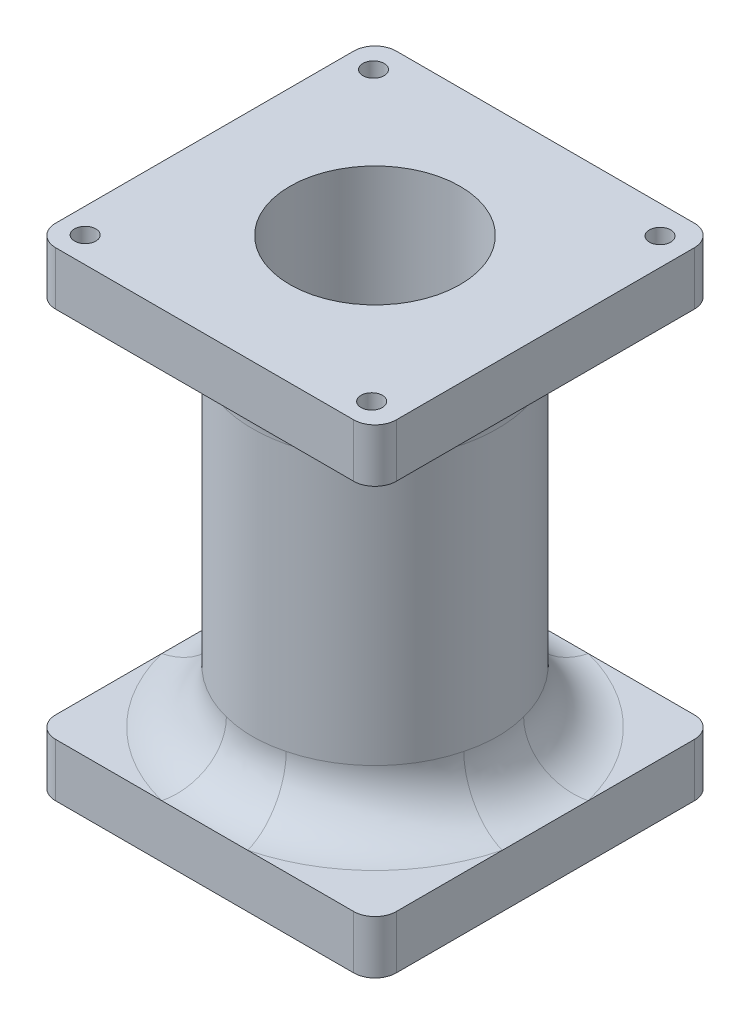
SolidWorks part; units mm, degrees
ref_plane "Front Plane" through (0, 0, 0) normal (0, 0, 1) x (1, 0, 0)
ref_plane "Top Plane" through (0, 0, 0) normal (0, 1, 0) x (1, 0, 0)
ref_plane "Right Plane" through (0, 0, 0) normal (1, 0, 0) x (0, 0, -1)
sketch "Sketch1" plane through (0, 0, 0) normal (0, 1, 0) x (1, 0, 0)
  line L1 (-14, 16) -> (14, 16)
  line L2 (-16, 14) -> (-16, -14)
  line L3 (-14, -16) -> (14, -16)
  line L4 (16, 14) -> (16, -14)
  line L5 (-16, 16) -> (16, -16) construction
  line L6 (-16, -16) -> (16, 16) construction
  arc A0 (-16, -14) -> (-14, -16) centre (-14, -14) ccw
  arc A1 (14, -16) -> (16, -14) centre (14, -14) ccw
  arc A2 (16, 14) -> (14, 16) centre (14, 14) ccw
  arc A3 (-14, 16) -> (-16, 14) centre (-14, 14) ccw
  point P0 (0, 0)
  dimension "D3" = 2
  dimension "D1" = 32
  dimension "D2" = 32
extrude "Boss-Extrude1" add sketch "Sketch1" along normal blind 5
sketch "Sketch2" plane through (0, 5, 0) normal (0, 1, 0) x (1, 0, 0)
  circle A0 centre (0, 0) radius 11.5
  dimension "D1" = 23
extrude "Boss-Extrude2" add sketch "Sketch2" along normal blind 35
sketch "Sketch3" plane through (0, 40, 0) normal (0, 1, 0) x (1, 0, 0)
  line L1 (-14, 16) -> (14, 16)
  line L2 (-16, 14) -> (-16, -14)
  line L3 (-14, -16) -> (14, -16)
  line L4 (16, 14) -> (16, -14)
  line L5 (-16, 16) -> (16, -16) construction
  line L6 (-16, -16) -> (16, 16) construction
  arc A0 (-16, -14) -> (-14, -16) centre (-14, -14) ccw
  arc A1 (14, -16) -> (16, -14) centre (14, -14) ccw
  arc A2 (16, 14) -> (14, 16) centre (14, 14) ccw
  arc A3 (-14, 16) -> (-16, 14) centre (-14, 14) ccw
  point P0 (0, 0)
  dimension "D3" = 2
  dimension "D1" = 32
  dimension "D2" = 32
extrude "Boss-Extrude3" add sketch "Sketch3" along normal blind 5
sketch "Sketch4" plane through (0, 0, 0) normal (0, -1, 0) x (1, 0, 0)
  circle A0 centre (-13.6513, 13.5733) radius 0.75
  circle A1 centre (13.3485, 13.6587) radius 0.75
  circle A2 centre (13.434, -13.3411) radius 0.75
  circle A3 centre (-13.5659, -13.4266) radius 0.75
  dimension "D1" = 1.5
extrude "Cut-Extrude1" cut sketch "Sketch4" against normal blind 3
sketch "Sketch5" plane through (0, 40, 0) normal (0, -1, 0) x (1, 0, 0)
  circle A0 centre (-13.6513, 13.5733) radius 1
  circle A1 centre (13.3485, 13.6587) radius 1
  circle A2 centre (-13.5659, -13.4266) radius 1
  circle A3 centre (13.434, -13.3411) radius 1
  dimension "D1" = 2
extrude "Cut-Extrude2" cut sketch "Sketch5" against normal up to next
chamfer "Chamfer1" distance 1 angle 45 4 edges at (13.434, 40, -14.3411) (-13.5659, 40, -14.4266) (13.3485, 40, 12.6587) (-13.6513, 40, 12.5733)
sketch "Sketch6" plane through (0, 0, 0) normal (0, -1, 0) x (1, 0, 0)
  circle A0 centre (0, 0) radius 8
  dimension "D1" = 16
extrude "Cut-Extrude3" cut sketch "Sketch6" against normal up to next
fillet "Fillet2" radius 5 2 edges at (0, 40, 11.5) (0, 5, 11.5)
